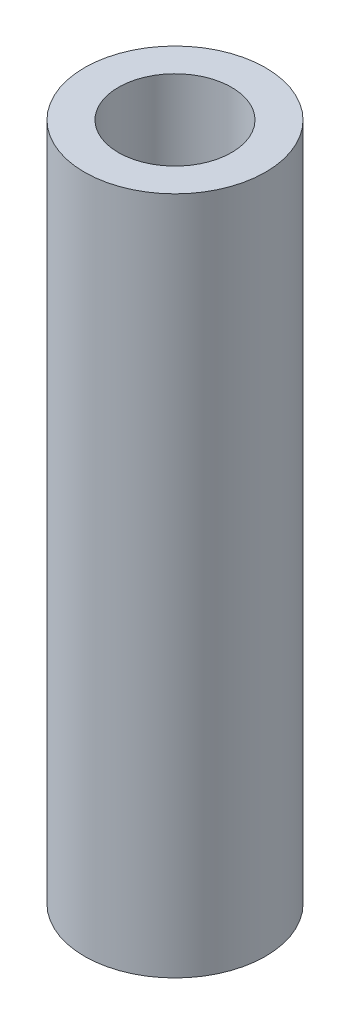
SolidWorks part; units mm, degrees
ref_plane "Front (XY)" through (0, 0, 0) normal (0, 0, 1) x (1, 0, 0)
ref_plane "Top (XZ)" through (0, 0, 0) normal (0, 1, 0) x (1, 0, 0)
ref_plane "Right (YZ)" through (0, 0, 0) normal (1, 0, 0) x (0, 0, -1)
sketch "Sketch1" plane through (0, 0, 0) normal (0, 1, 0) x (1, 0, 0)
  circle A0 centre (0, 0) radius 4
  dimension "D1" = 8
extrude "Boss-Extrude1" add sketch "Sketch1" along normal blind 30
sketch "Sketch2" plane through (0, 30, 0) normal (0, 1, 0) x (1, 0, 0)
  circle A2 centre (0, 0) radius 2.5
  circle A3 centre (0, 0) radius 2.5
  dimension "D1" = 1.5
extrude "Cut-Extrude1" cut sketch "Sketch2" against normal through all
